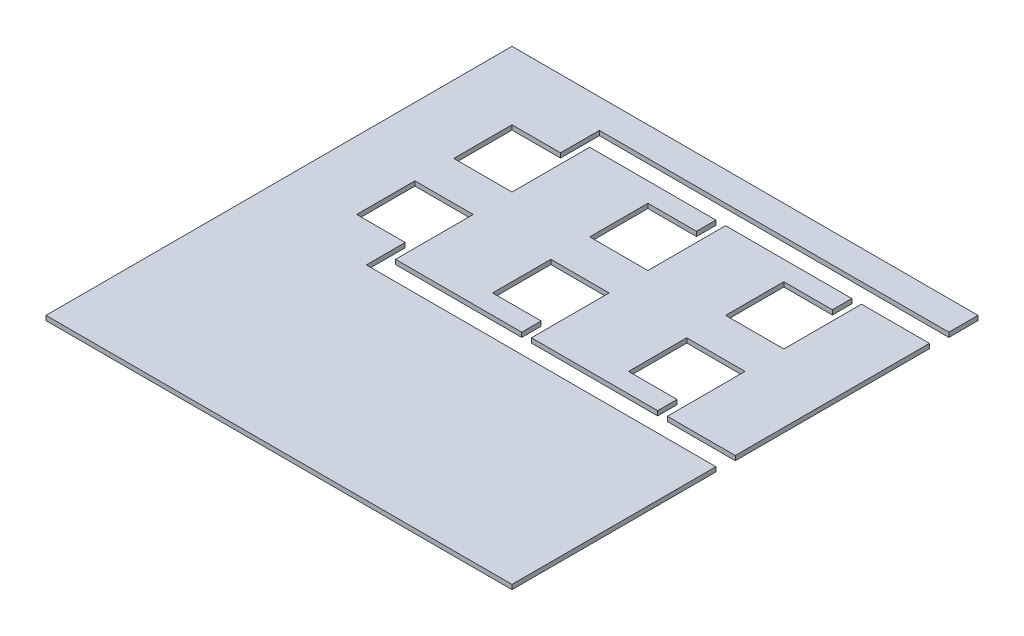
SolidWorks part; units mm, degrees
ref_plane "Front Plane" through (0, 0, 0) normal (0, 0, 1) x (1, 0, 0)
ref_plane "Top Plane" through (0, 0, 0) normal (0, 1, 0) x (1, 0, 0)
ref_plane "Right Plane" through (0, 0, 0) normal (1, 0, 0) x (0, 0, -1)
sketch "Sketch1" plane through (0, 0, 0) normal (0, 1, 0) x (1, 0, 0)
  line L1 (-152.4, -152.4) -> (152.4, -152.4)
  line L2 (-152.4, -152.4) -> (-152.4, 152.4)
  line L3 (-152.4, 152.4) -> (152.4, 152.4)
  line L4 (152.4, -152.4) -> (152.4, 152.4)
  line L5 (-152.4, -152.4) -> (152.4, 152.4) construction
  line L6 (-152.4, 152.4) -> (152.4, -152.4) construction
  point P0 (0, 0)
  dimension "D1" = 304.8
  dimension "D2" = 304.8
extrude "Boss-Extrude1" add sketch "Sketch1" along normal blind 2.9972
sketch "Sketch2" plane through (0, 2.9972, 0) normal (0, 1, 0) x (1, 0, 0)
  line L0 (152.4, 152.4) -> (-152.4, 152.4) construction
  line L1 (-107.95, 69.85) -> (-69.85, 69.85)
  line L2 (-107.95, 69.85) -> (-107.95, 107.95)
  line L3 (-107.95, 107.95) -> (-69.85, 107.95)
  line L4 (-69.85, 69.85) -> (-69.85, 107.95)
  line L5 (-107.95, 69.85) -> (-69.85, 107.95) construction
  line L6 (-107.95, 107.95) -> (-69.85, 69.85) construction
  line L7 (-152.4, 152.4) -> (-152.4, -152.4) construction
  point P0 (-88.9, 88.9)
  dimension "D1" = 38.1
  dimension "D2" = 38.1
  dimension "D3" = 44.45
  dimension "D4" = 44.45
extrude "Cut-Extrude1" cut sketch "Sketch2" against normal blind 2.9972
pattern_linear "LPattern1" count 3 spacing 88.9 along (1, 0, 0) count 2 spacing 63.5 along (0, 0, 1) of "Cut-Extrude1"
sketch "Sketch3" plane through (0, 2.9972, 0) normal (0, 1, 0) x (1, 0, 0)
  line L0 (-69.85, 107.95) -> (-69.85, 120.65)
  line L1 (-69.85, 120.65) -> (12.7, 120.65)
  line L2 (152.4, -152.4) -> (152.4, 152.4) construction
  line L3 (152.4, 120.65) -> (152.4, 133.35)
  line L4 (152.4, 133.35) -> (-76.2, 133.35)
  line L5 (-76.2, 133.35) -> (-76.2, 107.95)
  line L6 (-69.85, 107.95) -> (-107.95, 107.95) construction
  line L7 (-76.2, 107.95) -> (-69.85, 107.95)
  line L8 (19.05, 107.95) -> (19.05, 120.65)
  line L9 (12.7, 107.95) -> (12.7, 120.65)
  line L10 (19.05, 107.95) -> (-19.05, 107.95) construction
  line L11 (12.7, 107.95) -> (19.05, 107.95)
  line L13 (19.05, 120.65) -> (101.6, 120.65)
  line L14 (107.95, 107.95) -> (107.95, 120.65)
  line L16 (101.6, 120.65) -> (101.6, 107.95)
  line L17 (107.95, 107.95) -> (69.85, 107.95) construction
  line L18 (101.6, 107.95) -> (107.95, 107.95)
  line L19 (107.95, 120.65) -> (152.4, 120.65)
  line L20 (-69.85, 6.35) -> (-69.85, -6.35)
  line L21 (-107.95, 6.35) -> (-69.85, 6.35) construction
  line L22 (-69.85, 6.35) -> (-69.85, 44.45) construction
  line L23 (-69.85, -6.35) -> (12.7, -6.35)
  line L24 (12.7, -6.35) -> (12.7, 6.35)
  line L25 (-19.05, 6.35) -> (19.05, 6.35) construction
  line L26 (12.7, 6.35) -> (19.05, 6.35)
  line L27 (19.05, 6.35) -> (19.05, -6.35)
  line L28 (19.05, -6.35) -> (101.6, -6.35)
  line L29 (101.6, -6.35) -> (101.6, 6.35)
  line L30 (69.85, 6.35) -> (107.95, 6.35) construction
  line L31 (101.6, 6.35) -> (107.95, 6.35)
  line L32 (107.95, 6.35) -> (107.95, -6.35)
  line L33 (107.95, -6.35) -> (152.4, -6.35)
  line L34 (152.4, -6.35) -> (152.4, -19.05)
  line L35 (152.4, -19.05) -> (-76.2, -19.05)
  line L36 (-76.2, -19.05) -> (-76.2, 6.35)
  line L37 (-76.2, 6.35) -> (-69.85, 6.35)
  dimension "D1" = 6.35
  dimension "D2" = 6.35
  dimension "D3" = 6.35
  dimension "D4" = 12.7
  dimension "D5" = 12.7
  dimension "D6" = 6.35
  dimension "D7" = 6.35
  dimension "D8" = 6.35
  dimension "D9" = 12.7
  dimension "D10" = 12.7
  dimension "D11" = 12.7
  dimension "D12" = 12.7
extrude "Cut-Extrude2" cut sketch "Sketch3" against normal blind 2.9972
